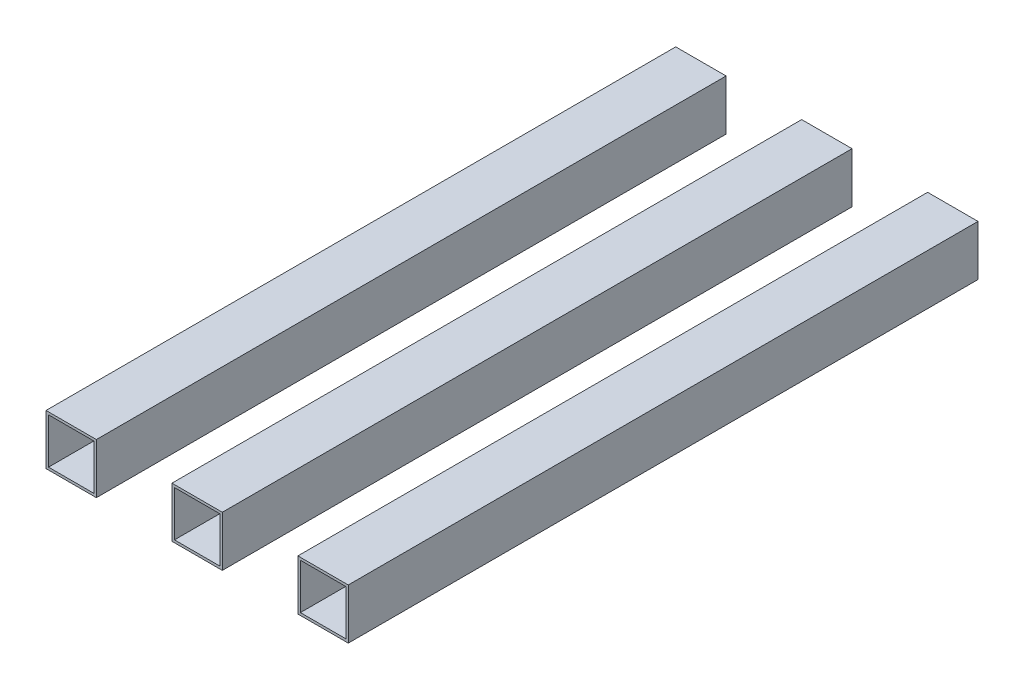
SolidWorks part; units mm, degrees
material "Труба 40х40х2,0 ГОСТ 8639-82 / Ст3сп ГОСТ 13663-86"
ref_plane "Спереди" through (0, 0, 0) normal (0, 0, 1) x (1, 0, 0)
ref_plane "Сверху" through (0, 0, 0) normal (0, 1, 0) x (1, 0, 0)
ref_plane "Справа" through (0, 0, 0) normal (1, 0, 0) x (0, 0, -1)
sketch "Эскиз1" plane through (0, 0, 0) normal (0, 0, 1) x (1, 0, 0)
  line L1 (-120, -20) -> (-80, -20)
  line L2 (-120, -20) -> (-120, 20)
  line L3 (-120, 20) -> (-80, 20)
  line L4 (-80, -20) -> (-80, 20)
  line L6 (-118, -18) -> (-82, -18)
  line L7 (-118, -18) -> (-118, 18)
  line L8 (-118, 18) -> (-82, 18)
  line L9 (-82, -18) -> (-82, 18)
extrude "Бобышка-Вытянуть1" add sketch "Эскиз1" along normal blind 500 separate body
sketch "Эскиз2" plane through (0, 0, 0) normal (0, 0, 1) x (1, 0, 0)
  line L1 (-20, -20) -> (20, -20)
  line L2 (-20, -20) -> (-20, 20)
  line L3 (-20, 20) -> (20, 20)
  line L4 (20, -20) -> (20, 20)
  line L6 (-18, -18) -> (18, -18)
  line L7 (-18, -18) -> (-18, 18)
  line L8 (-18, 18) -> (18, 18)
  line L9 (18, -18) -> (18, 18)
extrude "Бобышка-Вытянуть2" add sketch "Эскиз2" along normal blind 500 separate body
sketch "Эскиз3" plane through (0, 0, 0) normal (0, 0, 1) x (1, 0, 0)
  line L1 (80, -20) -> (120, -20)
  line L2 (80, -20) -> (80, 20)
  line L3 (80, 20) -> (120, 20)
  line L4 (120, -20) -> (120, 20)
  line L6 (82, -18) -> (118, -18)
  line L7 (82, -18) -> (82, 18)
  line L8 (82, 18) -> (118, 18)
  line L9 (118, -18) -> (118, 18)
extrude "Бобышка-Вытянуть3" add sketch "Эскиз3" along normal blind 500 separate body
